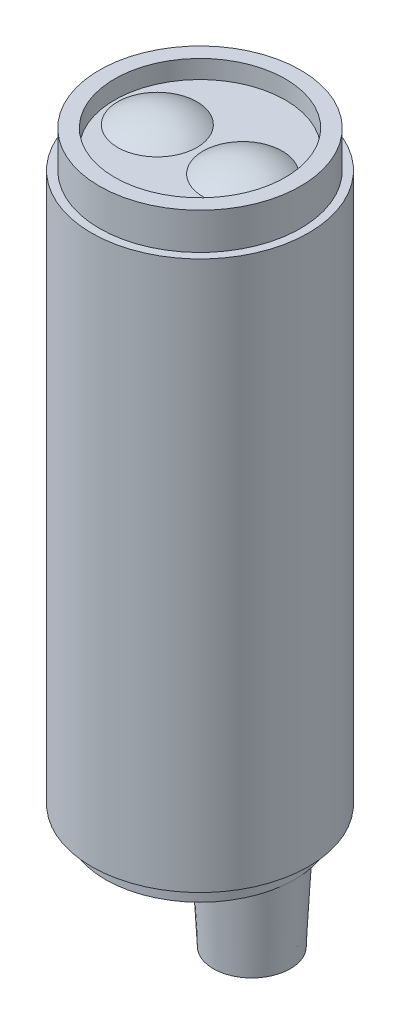
SolidWorks part; units mm, degrees
ref_plane "Front Plane" through (0, 0, 0) normal (0, 0, 1) x (1, 0, 0)
ref_plane "Top Plane" through (0, 0, 0) normal (0, 1, 0) x (1, 0, 0)
ref_plane "Right Plane" through (0, 0, 0) normal (1, 0, 0) x (0, 0, -1)
sketch "Sketch1" plane through (0, 0, 0) normal (0, 1, 0) x (1, 0, 0)
  circle A0 centre (0, 0) radius 8.9
  dimension "D1" = 17.8
extrude "Boss-Extrude1" add sketch "Sketch1" along normal blind 45
sketch "Sketch2" plane through (0, 45, 0) normal (0, 1, 0) x (1, 0, 0)
  circle A0 centre (0, 0) radius 7
  circle A1 centre (0, 0) radius 8.25
  dimension "D1" = 16.5
  dimension "D2" = 14
extrude "Boss-Extrude2" add sketch "Sketch2" along normal blind 3
sketch "Sketch3" plane through (0, 45, 0) normal (0, 1, 0) x (1, 0, 0)
  circle A0 centre (0, 0) radius 7 construction
  circle A1 centre (0, 0) radius 7
extrude "Boss-Extrude3" add sketch "Sketch3" along normal blind 1.5
sketch "Sketch4" plane through (0, 46.5, 0) normal (0, 1, 0) x (1, 0, 0)
  line L0 (-3.5, 0) -> (3.5, 0) construction
  circle A0 centre (-3.5, 0) radius 3.25
  circle A1 centre (3.5, 0) radius 3.25
  point P4 (0, 0)
  dimension "D2" = 6.5
  dimension "D3" = 6.5
  dimension "D1" = 7
sketch "Sketch5" plane through (0, 0, 0) normal (0, 0, 1) x (1, 0, 0)
  line L1 (-3.5, 46.5) -> (-3.5, 47.5)
  line L3 (-3.5, 46.5) -> (-3.5, 47.5) construction
  line L10 (-0.25, 46.5) -> (-6.75, 46.5) construction
  line L11 (-0.25, 46.5) -> (-3.5, 46.5)
  arc A0 (-3.5, 47.5) -> (-0.25, 46.5) centre (-3.5, 41.7188) cw
  dimension "D1" = 1
revolve "Revolve5" add sketch "Sketch5" angle 360 about L3
mirror "Mirror1" about plane through (0, 0, 0) normal (1, 0, 0) of "Revolve5"
sketch "Sketch6" plane through (0, 0, 0) normal (0, -1, 0) x (1, 0, 0)
  circle A0 centre (0, 0) radius 7.75
  dimension "D1" = 15.5
extrude "Boss-Extrude4" add sketch "Sketch6" along normal blind 1.5 separate body
sketch "Sketch7" plane through (0, -1.5, 0) normal (0, -1, 0) x (1, 0, 0)
  circle A0 centre (4.25, 0) radius 3.5
  circle A1 centre (0, 0) radius 7.75 construction
  dimension "D1" = 7
extrude "Boss-Extrude5" add sketch "Sketch7" along normal blind 6.5 draft 3
ref_plane "Plane1" through (0, -10, 0) normal (0, -1, 0) x (-1, 0, 0)
sketch "Sketch8" plane through (0, -10, 0) normal (0, -1, 0) x (-1, 0, 0)
  circle A0 centre (0, 0) radius 8.9 construction
  circle A1 centre (0, 0) radius 8.9
curve "Helix/Spiral1" pitch 0.35 height 56 turns 160
